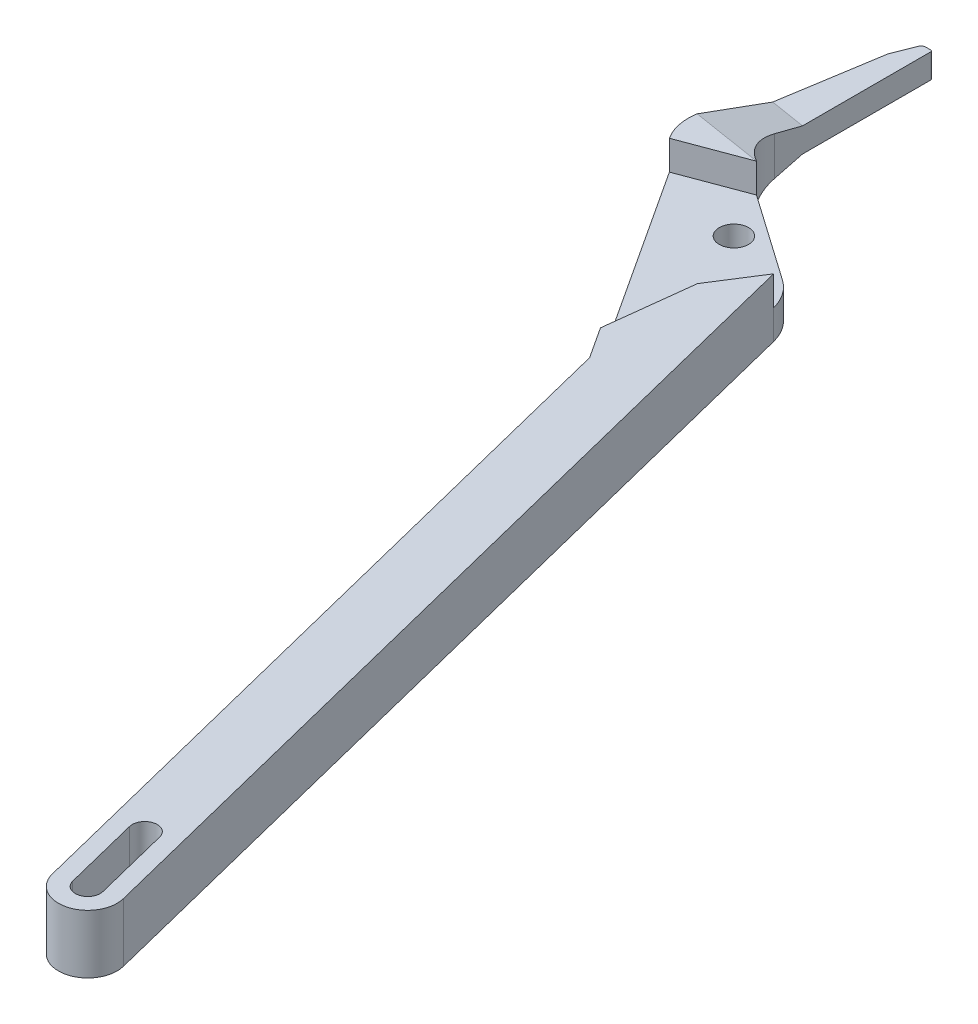
SolidWorks part; units mm, degrees
material "6061-T6 (SS)"
ref_plane "Front Plane" through (0, 0, 0) normal (0, 0, 1) x (1, 0, 0)
ref_plane "Top Plane" through (0, 0, 0) normal (0, 1, 0) x (1, 0, 0)
ref_plane "Right Plane" through (0, 0, 0) normal (1, 0, 0) x (0, 0, -1)
sketch "Sketch1" plane through (0, 0, 0) normal (0, 1, 0) x (1, 0, 0)
  line L0 (4.5666, -9.3015) -> (-20.0079, 7.9058)
  line L5 (-5.7358, 10.1201) -> (12.7996, -2.8585)
  line L9 (16.7668, -8.6308) -> (60.9657, -185.9031)
  line L10 (60.9657, -185.9031) -> (49.3222, -188.8062)
  line L11 (49.3222, -188.8062) -> (4.5666, -9.3015)
  line L12 (-17.9281, 4.7213) -> (12.8013, -42.3291)
  line L13 (55.1439, -187.3546) -> (51.2732, -171.8299) construction
  line L14 (52.6697, -187.9715) -> (48.7989, -172.4468)
  line L15 (57.6182, -186.7377) -> (53.7474, -171.213)
  line L16 (-10.25, 50.6059) -> (-11.323, 50.6059)
  line L17 (-12.2514, 49.9773) -> (-13.8762, 45.9156)
  line L18 (-5.7358, 10.1201) -> (-10, 13.1059)
  line L19 (-14.0528, 45.2767) -> (-19.4457, 11.6676)
  line L20 (-10, 50.3559) -> (-10, 13.1059)
  circle A0 centre (0, 0) radius 3
  circle A1 centre (55.1439, -187.3546) radius 6
  arc A2 (52.6697, -187.9715) -> (57.6182, -186.7377) centre (55.1439, -187.3546) ccw
  arc A3 (53.7474, -171.213) -> (48.7989, -172.4468) centre (51.2732, -171.8299) ccw
  arc A7 (-10, 18.3116) -> (-5.7358, 10.1201) centre (0, 18.3116) ccw
  arc A8 (12.7996, -2.8585) -> (16.7668, -8.6308) centre (7.0638, -11.05) cw
  arc A9 (-17.9281, 4.7213) -> (-19.4457, 11.6676) centre (-9.5556, 10.1895) cw
  arc A10 (-10, 50.3559) -> (-10.25, 50.6059) centre (-10.25, 50.3559) ccw
  arc A11 (-12.2514, 49.9773) -> (-11.323, 50.6059) centre (-11.323, 49.6059) cw
  arc A12 (-14.0528, 45.2767) -> (-13.8762, 45.9156) centre (-11.0907, 44.8014) cw
  point P13 (53.2086, -179.5923)
  point P32 (-10, 13.1059)
  point P44 (-10, 50.6059)
  point P47 (-12, 50.6059)
  point P50 (-14, 45.6059)
  dimension "D7" = 4.5666
  dimension "D19" = 4.7213
  dimension "D17" = 14
  dimension "D5" = 0.25
  dimension "D10" = 12.8013
  dimension "D31" = 19.4457
  dimension "D1" = 6
  dimension "D2" = 12
  dimension "D3" = 2.55
  dimension "D4" = 10
  dimension "D6" = 1
  dimension "D8" = 7.0638
  dimension "D9" = 12.7996
  dimension "D11" = 48.7989
  dimension "D12" = 49.3222
  dimension "D13" = 9.5556
  dimension "D14" = 11.0907
  dimension "D15" = 11.323
  dimension "D16" = 12
  dimension "D18" = 17.9281
extrude "Boss-Extrude2" add sketch "Sketch1" along normal blind 12
sketch "Sketch3" plane through (-20.8186, 0, -3.1119) normal (-0.9874, 0, -0.1584) x (-0.1584, 0, 0.9874)
  line L0 (-0.2258, 0) -> (-57.3843, 0)
  line L1 (-8.891, 6) -> (-57.3843, 6)
  line L3 (-57.3843, 0) -> (-57.3843, 12)
  line L4 (-8.891, 6) -> (-8.891, 0)
  line L5 (-8.891, 0) -> (-22.3843, 3.5)
  line L6 (-22.3843, 3.5) -> (-57.3843, 3.5)
  line L7 (-0.2258, 12) -> (-57.3843, 12)
  line L8 (-8.891, 12) -> (-22.3843, 8.5)
  line L9 (-22.3843, 8.5) -> (-57.3843, 8.5)
  line L10 (-0.2258, 0) -> (-0.2258, 12)
  dimension "D1" = 8.6652
  dimension "D2" = 22.1585
  dimension "D3" = 57.1585
  dimension "D4" = 3.5
  dimension "D5" = 6
extrude "Cut-Extrude1" cut sketch "Sketch3" against normal through all
sketch "Sketch4" plane through (0, 12, 0) normal (0, 1, 0) x (1, 0, 0)
  line L2 (-4.9508, 9.5704) -> (-17.9281, 4.7213)
  line L3 (-17.9281, 4.7213) -> (12.8013, -42.3291)
  line L4 (12.8013, -42.3291) -> (16.7668, -8.6308)
  line L5 (16.7668, -8.6308) -> (17.4322, -2.9762)
  line L6 (17.4322, -2.9762) -> (-4.9508, 9.5704)
  line L7 (8.6208, -35.9281) -> (12.8037, -0.3817)
  line L8 (16.7668, -8.6308) -> (10.7122, -18.1549)
  circle M5 centre (0, 0) radius 3
  line M9 (-17.9281, 4.7213) -> (12.8013, -42.3291)
  arc M13 (16.7668, -8.6308) -> (12.7996, -2.8585) centre (7.0638, -11.05) ccw
  line M14 (12.7996, -2.8585) -> (-4.9508, 9.5704)
  dimension "D1" = 5.6546
  dimension "D2" = 0
  dimension "D3" = 4.9
extrude "Cut-Extrude4" cut sketch "Sketch4" against normal blind 6 contours L7 L2 M9 M13 M14 M5 | L8 L7 M13
equation "\"weightkg\"= \"SW-Mass\" / 1000"
